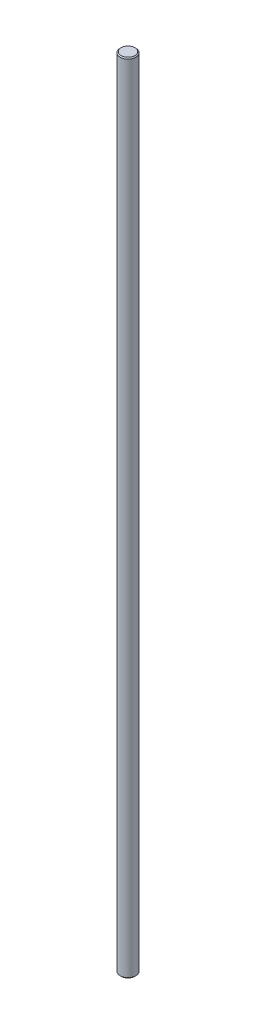
SolidWorks part; units mm, degrees
ref_plane "Front Plane" through (0, 0, 0) normal (0, 0, 1) x (1, 0, 0)
ref_plane "Top Plane" through (0, 0, 0) normal (0, 1, 0) x (1, 0, 0)
ref_plane "Right Plane" through (0, 0, 0) normal (1, 0, 0) x (0, 0, -1)
sketch "Sketch1" plane through (0, 0, 0) normal (0, 0, 1) x (1, 0, 0)
  line L0 (3.5, 406) -> (0, 406)
  line L1 (0, 406) -> (0, 0)
  line L2 (0, 0) -> (3.5, 0)
  line L3 (3.5, 0) -> (4, 0.5)
  line L4 (4, 0.5) -> (4, 405.5)
  line L5 (4, 405.5) -> (3.5, 406)
  line L6 (0, 406) -> (0, 0) construction
revolve "Revolve1" add sketch "Sketch1" angle 360 about L6
